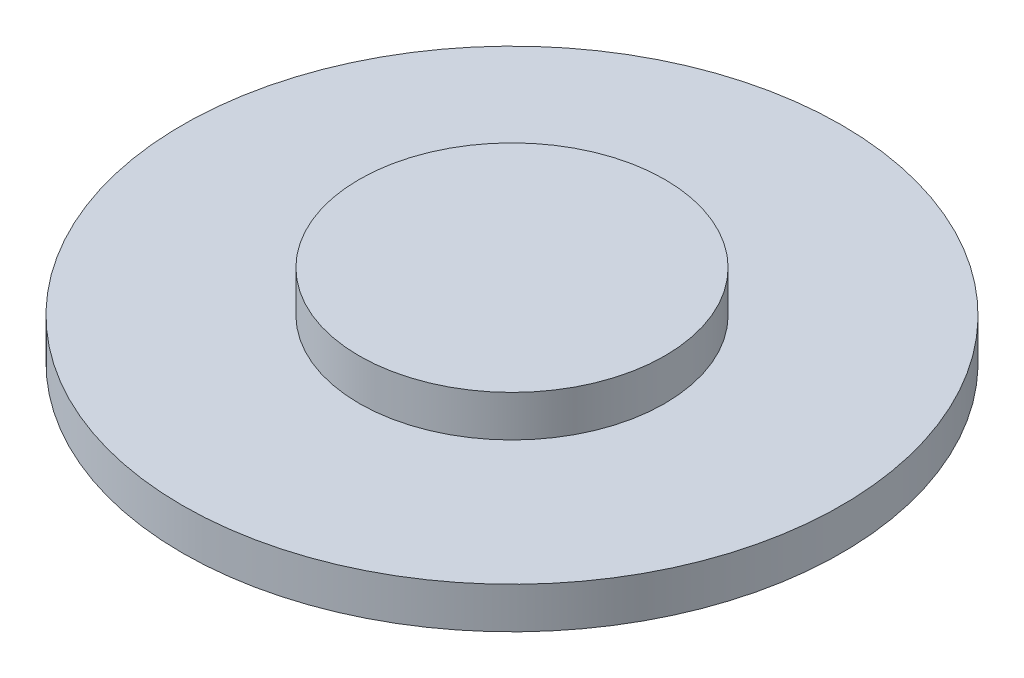
SolidWorks part; units mm, degrees
ref_plane "Plano frontal" through (0, 0, 0) normal (0, 0, 1) x (1, 0, 0)
ref_plane "Plano superior" through (0, 0, 0) normal (0, 1, 0) x (1, 0, 0)
ref_plane "Plano direito" through (0, 0, 0) normal (1, 0, 0) x (0, 0, -1)
ref_plane "Plano1" through (0, 0, 0) normal (0, 0, -1) x (-1, 0, 0)
sketch "Esboço1" plane through (0, 0, 0) normal (0, 0, -1) x (-1, 0, 0)
  line L0 (-40, -5) -> (0, -5)
  line L1 (0, -5) -> (0, 5)
  line L2 (0, 5) -> (-18.55, 5)
  line L3 (-18.55, 5) -> (-18.55, 0)
  line L4 (-18.55, 0) -> (-40, 0)
  line L5 (-40, 0) -> (-40, -5)
  line L6 (0, -5) -> (0, 5) construction
revolve "Revolução1" add sketch "Esboço1" angle 360 about L6
